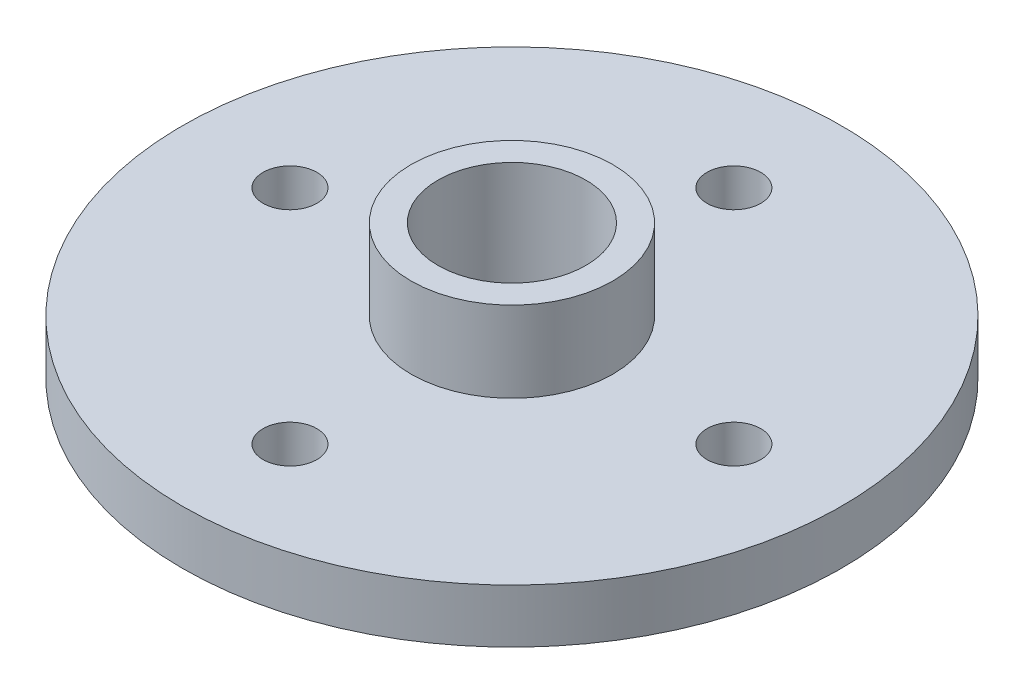
SolidWorks part; units mm, degrees
material "1060 Alloy"
ref_plane "Front Plane" through (0, 0, 0) normal (0, 0, 1) x (1, 0, 0)
ref_plane "Top Plane" through (0, 0, 0) normal (0, 1, 0) x (1, 0, 0)
ref_plane "Right Plane" through (0, 0, 0) normal (1, 0, 0) x (0, 0, -1)
sketch "Sketch2" plane through (0, 0, 0) normal (0, 1, 0) x (1, 0, 0)
  circle A0 centre (0, 0) radius 12.25
  dimension "D1" = 24.5
extrude "Boss-Extrude1" add sketch "Sketch2" along normal blind 2
sketch "Sketch3" plane through (0, 2, 0) normal (0, 1, 0) x (1, 0, 0)
  line L0 (0, 0) -> (0, 12.6294) construction
  line L1 (0, 0) -> (16.4383, 0) construction
  circle A1 centre (0, 8.25) radius 1
  circle A2 centre (8.25, 0) radius 1
  circle A3 centre (0, -8.25) radius 1
  circle A4 centre (-8.25, 0) radius 1
  dimension "D1" = 16.5
  dimension "D3" = 2
  dimension "D2" = 16.5
extrude "Cut-Extrude1" cut sketch "Sketch3" against normal through all
sketch "Sketch4" plane through (0, 2, 0) normal (0, 1, 0) x (1, 0, 0)
  circle A0 centre (0, 0) radius 3.75
  dimension "D1" = 7.5
extrude "Boss-Extrude2" add sketch "Sketch4" along normal blind 3
sketch "Sketch5" plane through (0, 5, 0) normal (0, 1, 0) x (1, 0, 0)
  circle A0 centre (0, 0) radius 1.5
  dimension "D1" = 3
extrude "Cut-Extrude2" cut sketch "Sketch5" against normal through all
sketch "Sketch6" plane through (0, 5, 0) normal (0, 1, 0) x (1, 0, 0)
  circle A0 centre (0, 0) radius 2.75
  dimension "D1" = 5.5
extrude "Cut-Extrude3" cut sketch "Sketch6" against normal blind 4.5
